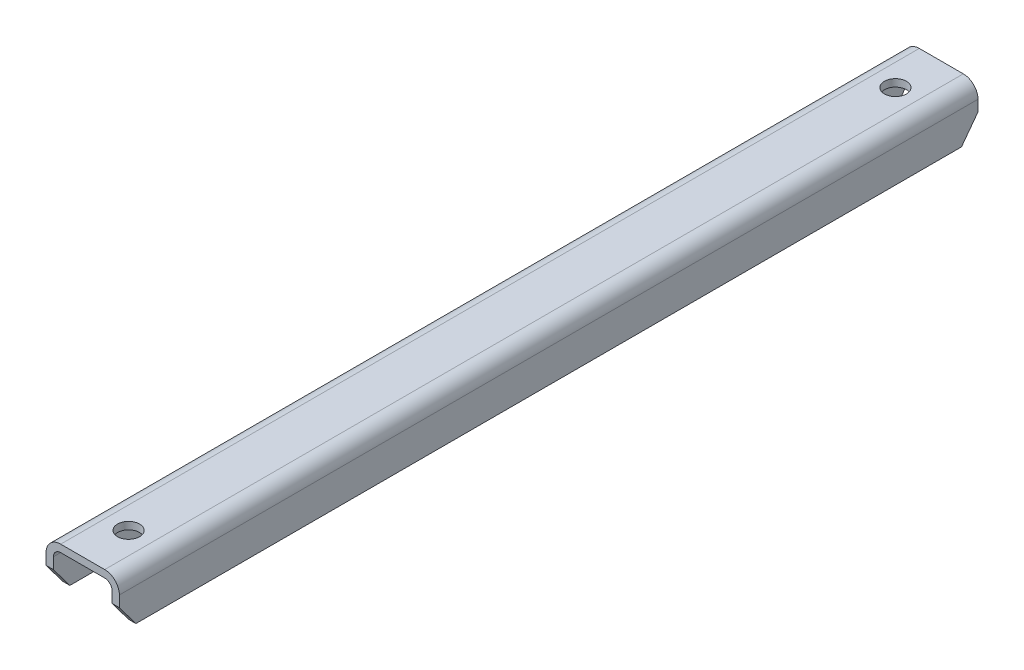
SolidWorks part; units mm, degrees
material "3.0205 (EN-AW 1200)"
ref_plane "前视基准面" through (0, 0, 0) normal (0, 0, 1) x (1, 0, 0)
ref_plane "上视基准面" through (0, 0, 0) normal (0, 1, 0) x (1, 0, 0)
ref_plane "右视基准面" through (0, 0, 0) normal (1, 0, 0) x (0, 0, -1)
sketch "草图1" plane through (0, 0, 0) normal (0, 0, 1) x (1, 0, 0)
  line L0 (-30, 0) -> (30, 0)
  line L1 (50, -20) -> (50, -65)
  line L2 (-50, -20) -> (-50, -65)
  line L3 (-40, -20) -> (-40, -65)
  line L4 (-30, -10) -> (30, -10)
  line L5 (40, -20) -> (40, -65)
  line L6 (-40, -65) -> (-50, -65)
  line L7 (40, -65) -> (50, -65)
  arc A0 (30, 0) -> (50, -20) centre (30, -20) cw
  arc A1 (-30, 0) -> (-50, -20) centre (-30, -20) ccw
  arc A2 (-30, -10) -> (-40, -20) centre (-30, -20) ccw
  arc A3 (30, -10) -> (40, -20) centre (30, -20) cw
  point P7 (50, 0)
  point P10 (-50, 0)
  dimension "D3" = 20
  dimension "D1" = 65
  dimension "D2" = 100
  dimension "D4" = 10
extrude "凸台-拉伸1" add sketch "草图1" along normal mid plane 1170
sketch "草图2" plane through (0, 0, 0) normal (1, 0, 0) x (0, 0, -1)
  line L0 (-585, -35) -> (-585, -65)
  line L1 (-585, -65) -> (-585, -20) construction
  line L2 (-585, -65) -> (-562.5, -65)
  line L3 (-585, -65) -> (585, -65) construction
  line L4 (-562.5, -65) -> (-585, -35)
  line L5 (0, 0) -> (0, -149.8598) construction
  line L6 (562.5, -65) -> (585, -35)
  line L7 (585, -65) -> (562.5, -65)
  line L8 (585, -35) -> (585, -65)
  dimension "D1" = 30
  dimension "D2" = 22.5
extrude "切除-拉伸1" cut sketch "草图2" against normal mid plane 700
sketch "草图3" plane through (0, 0, 0) normal (0, 1, 0) x (1, 0, 0)
  line L0 (-87.5608, 522.5) -> (211.0841, 522.5) construction
  line L1 (-154.795, -522.5) -> (268.9367, -522.5) construction
  line L2 (0, -277.4831) -> (0, 378.5038) construction
  line L3 (-114.4483, 0) -> (171.619, 0) construction
  circle A0 centre (0, 522.5) radius 15
  circle A1 centre (0, -522.5) radius 15
  dimension "D3" = 30
  dimension "D4" = 30
  dimension "D1" = 1045
extrude "切除-拉伸2" cut sketch "草图3" against normal through all
